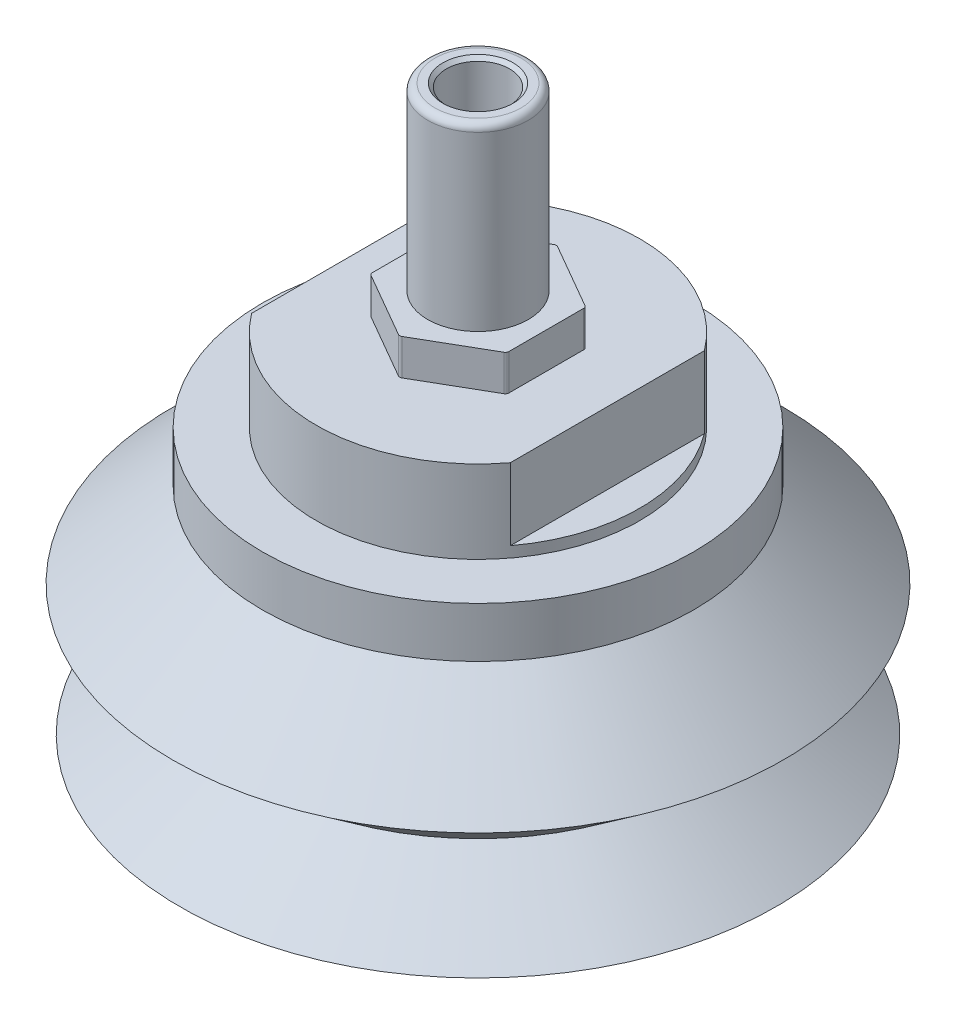
SolidWorks part; units mm, degrees
ref_plane "前视基准面" through (0, 0, 0) normal (0, 0, 1) x (1, 0, 0)
ref_plane "上视基准面" through (0, 0, 0) normal (0, 1, 0) x (1, 0, 0)
ref_plane "右视基准面" through (0, 0, 0) normal (1, 0, 0) x (0, 0, -1)
other "Configuration Table"
sketch "草图1" plane through (0, 0, 0) normal (0, 0, 1) x (1, 0, 0)
  line L0 (0, 0) -> (0, 103.3354) construction
  line L1 (-40.5, 0) -> (-41.5, 0)
  line L2 (-41.5, 0) -> (-30, 8.6518)
  line L3 (-30, 8.6518) -> (-42.5, 18.1785)
  line L4 (-42.5, 18.1785) -> (-30, 30)
  line L5 (-30, 30) -> (-30, 37)
  line L6 (-30, 37) -> (-22.5, 37)
  line L7 (-22.5, 37) -> (-22.5, 48.5)
  line L8 (-22.5, 48.5) -> (-7, 48.5)
  line L9 (-7, 48.5) -> (-7, 78.5)
  line L10 (-7, 78.5) -> (0, 78.5)
  line L11 (0, 30) -> (0, 78.5)
  line L12 (-40.5, 0) -> (-29, 8.6518)
  line L13 (-29, 8.6518) -> (-41.5, 18.1785)
  line L14 (-41.5, 18.1785) -> (-29, 30)
  line L15 (-29, 30) -> (0, 30)
  dimension "D1" = 83
  dimension "D2" = 60
  dimension "D3" = 85
  dimension "D4" = 37
  dimension "D5" = 30
  dimension "D6" = 60
  dimension "D7" = 48.5
  dimension "D8" = 45
  dimension "D9" = 14
  dimension "D10" = 78.5
  dimension "D11" = 1
  dimension "D12" = 1
  dimension "D13" = 1
  dimension "D14" = 1
revolve "旋转2" add sketch "草图1" angle 360 about L0
cosmetic thread "装饰螺纹线1" parameters "D2"=11.835
sketch "草图4" plane through (0, 78.5, 0) normal (0, 1, 0) x (1, 0, 0)
  point P0 (0, 0)
hole_wizard "G1/8 螺纹孔1" positions "草图4" profile "草图3" tap size "G1/8" standard "GB" end condition through all
sketch "草图3" plane through (0, 78.5, 0) normal (1, 0, 0) x (0, 0, 1)
  line L0 (0, 0) -> (0, 78.5)
  line L1 (0, 78.5) -> (4.4, 78.5)
  line L2 (4.4, 78.5) -> (4.4, 0.489)
  line L3 (4.4, 0.489) -> (4.889, 0)
  line L5 (4.889, 0) -> (0, 0)
  line L6 (-4.4, 0.489) -> (-4.889, 0) construction
  line L11 (0, -6.35) -> (0, 107.95) construction
  dimension "通孔螺纹孔钻头直径" = 8.8
  dimension "通孔螺纹孔钻头深度" = 78.5
  dimension "近端锥形沉头孔直径" = 9.778
  dimension "近端锥形沉头孔角度" = 90
cosmetic thread "孔螺纹线1" parameters "D2"=9.728
fillet "圆角1" radius 1 1 edges at (0, 78.5, -7)
sketch "草图5" plane through (0, 48.5, 0) normal (0, 1, 0) x (1, 0, 0)
  line L0 (0, 0) -> (0, 38.1706) construction
  line L1 (-18, -31.9977) -> (-50.8963, -31.9977)
  line L2 (18, 32.3884) -> (50.8963, 32.3884)
  line L3 (18, 32.3884) -> (18, -31.9977)
  line L4 (18, -31.9977) -> (50.8963, -31.9977)
  line L5 (50.8963, 32.3884) -> (50.8963, -31.9977)
  line L6 (-50.8963, 32.3884) -> (-50.8963, -31.9977)
  line L7 (-18, 32.3884) -> (-50.8963, 32.3884)
  line L8 (-18, 32.3884) -> (-18, -31.9977)
  dimension "D1" = 18
extrude "切除-拉伸1" cut sketch "草图5" against normal blind 10
sketch "草图6" plane through (0, 48.5, 0) normal (0, 1, 0) x (1, 0, 0)
  line L1 (0, 10.9697) -> (-9.5, 5.4848)
  line L2 (-9.5, 5.4848) -> (-9.5, -5.4848)
  line L3 (-9.5, -5.4848) -> (0, -10.9697)
  line L4 (0, -10.9697) -> (9.5, -5.4848)
  line L5 (9.5, -5.4848) -> (9.5, 5.4848)
  line L6 (9.5, 5.4848) -> (0, 10.9697)
  circle A0 centre (0, 0) radius 9.5 construction
  circle A1 centre (0, 0) radius 4.4
  dimension "D1" = 19
extrude "凸台-拉伸1" add sketch "草图6" along normal blind 5
fillet "圆角2" radius 0.5 6 edges at (0, 51, 10.9697) (9.5, 51, 5.4848) (9.5, 51, -5.4848) (0, 51, -10.9697) (-9.5, 51, -5.4848) (-9.5, 51, 5.4848)
